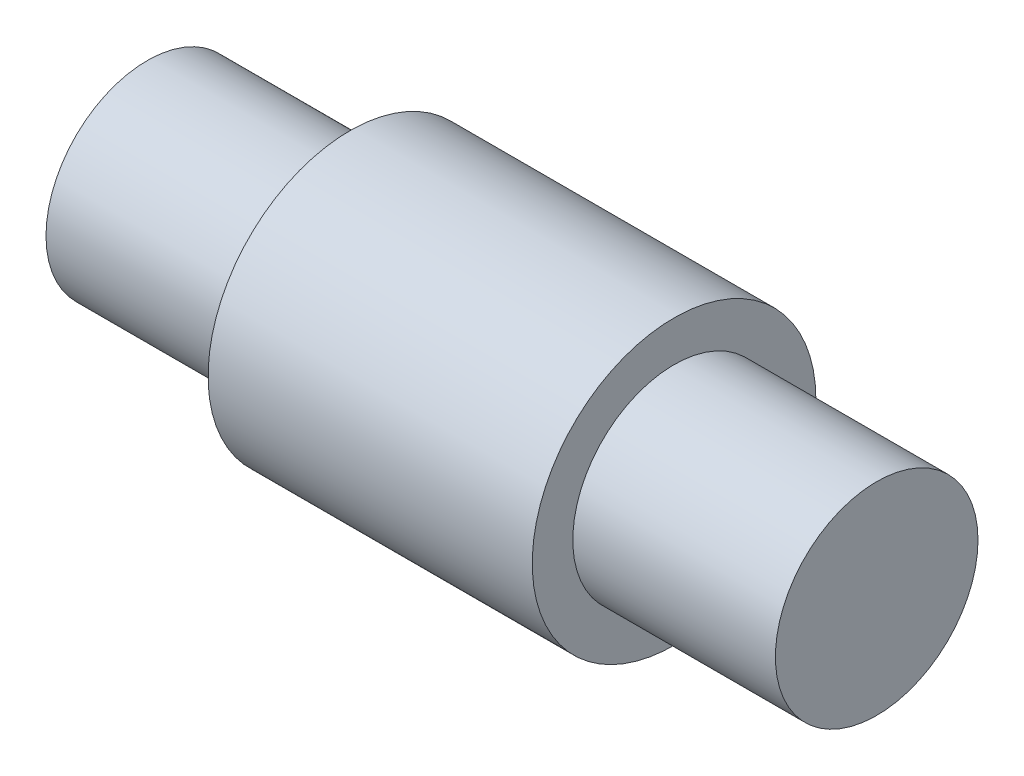
SolidWorks part; units mm, degrees
ref_plane "Front Plane" through (0, 0, 0) normal (0, 0, 1) x (1, 0, 0)
ref_plane "Top Plane" through (0, 0, 0) normal (0, 1, 0) x (1, 0, 0)
ref_plane "Right Plane" through (0, 0, 0) normal (1, 0, 0) x (0, 0, -1)
sketch "Sketch1" plane through (0, 0, 0) normal (1, 0, 0) x (0, 0, -1)
  circle A0 centre (0, 0) radius 7
  dimension "D1" = 14
extrude "Boss-Extrude1" add sketch "Sketch1" along normal blind 16
sketch "Sketch2" plane through (16, 0, 0) normal (1, 0, 0) x (0, 0, -1)
  circle A0 centre (0, 0) radius 5
  dimension "D1" = 10
extrude "Boss-Extrude2" add sketch "Sketch2" along normal blind 10
sketch "Sketch3" plane through (0, 0, 0) normal (-1, 0, 0) x (0, 0, 1)
  circle A0 centre (0, 0) radius 5
  dimension "D1" = 10
extrude "Boss-Extrude3" add sketch "Sketch3" along normal blind 10
